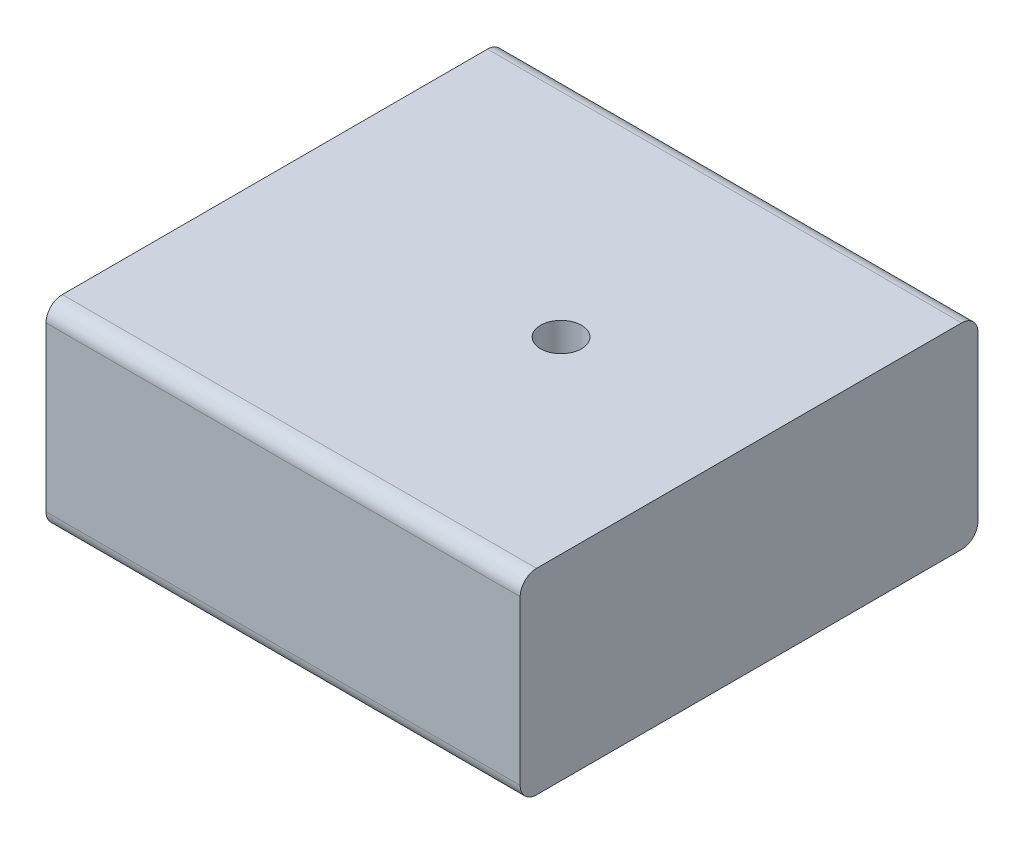
SolidWorks part; units mm, degrees
material "Pine"
ref_plane "Front Plane" through (0, 0, 0) normal (0, 0, 1) x (1, 0, 0)
ref_plane "Top Plane" through (0, 0, 0) normal (0, 1, 0) x (1, 0, 0)
ref_plane "Right Plane" through (0, 0, 0) normal (1, 0, 0) x (0, 0, -1)
sketch "Sketch1" plane through (0, 0, 0) normal (0, 0, 1) x (1, 0, 0)
  line L1 (-46.0375, 38.1) -> (46.0375, 38.1)
  line L2 (-46.0375, 38.1) -> (-46.0375, 0)
  line L3 (-46.0375, 0) -> (46.0375, 0)
  line L4 (46.0375, 38.1) -> (46.0375, 0)
  point P4 (0, 0)
  dimension "D1" = 92.075
  dimension "D2" = 38.1
extrude "Boss-Extrude1" add sketch "Sketch1" along normal blind 88.9
fillet "Fillet1" radius 3.175 4 edges at (0, 0, 0) (0, 0, 88.9) (0, 38.1, 0) (0, 38.1, 88.9)
sketch "Sketch2" plane through (0, 38.1, 0) normal (0, 1, 0) x (1, 0, 0)
  line L0 (-46.0375, -85.725) -> (-46.0375, -3.175) construction
  point P0 (9.525, -44.45)
  point P5 (-46.0375, -44.45)
  dimension "D1" = 55.5625
hole_wizard "5/16 (0.3125) Diameter Hole1" positions "Sketch3" profile "Sketch4" hole size "5/16" standard "ANSI Inch" end condition up to next
sketch "Sketch3" plane through (0, 38.1, 0) normal (0, 1, 0) x (1, 0, 0)
  point P0 (9.525, -44.45)
sketch "Sketch4" plane through (9.525, 38.1, 44.45) normal (1, 0, 0) x (0, 0, 1)
  line L0 (0, 0) -> (0, 38.1)
  line L1 (0, 38.1) -> (3.9687, 38.1)
  line L2 (3.9687, 38.1) -> (3.9687, 0)
  line L5 (3.9687, 0) -> (0, 0)
  line L11 (0, -6.35) -> (0, 107.95) construction
  dimension "Thru Hole Dia." = 7.9375
  dimension "Thru Hole Depth" = 38.1
